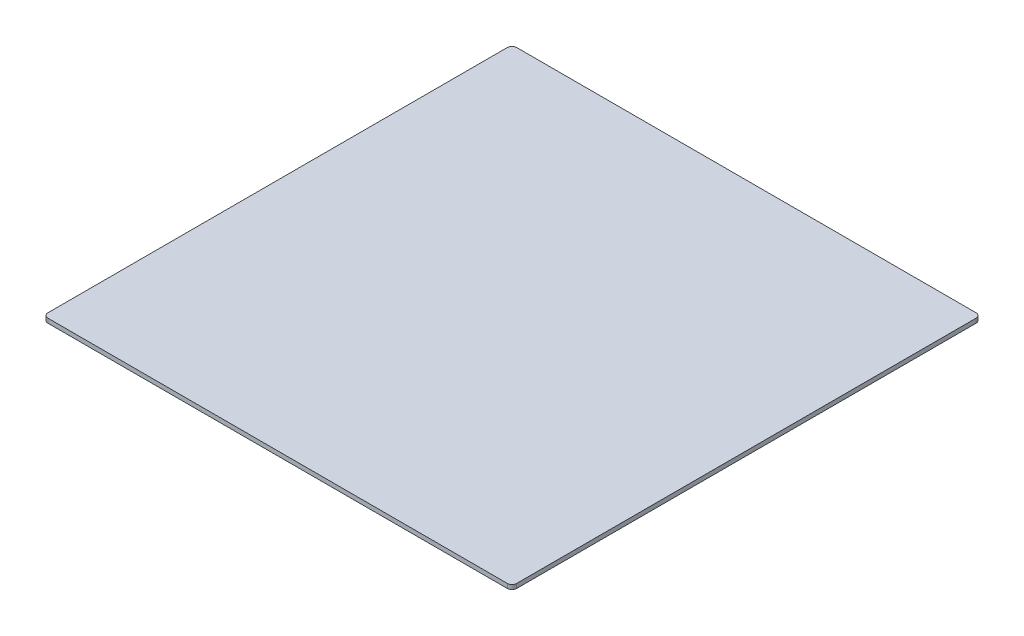
SolidWorks part; units mm, degrees
ref_plane "Front Plane" through (0, 0, 0) normal (0, 0, 1) x (1, 0, 0)
ref_plane "Top Plane" through (0, 0, 0) normal (0, 1, 0) x (1, 0, 0)
ref_plane "Right Plane" through (0, 0, 0) normal (1, 0, 0) x (0, 0, -1)
sketch "Sketch1" plane through (0, 0, 0) normal (0, 1, 0) x (1, 0, 0)
  line L5 (-50, 50) -> (50, 50)
  line L6 (-50, 50) -> (-50, -50)
  line L7 (-50, -50) -> (50, -50)
  line L8 (50, 50) -> (50, -50)
  line L9 (-50, 50) -> (50, -50) construction
  line L10 (-50, -50) -> (50, 50) construction
  point P0 (0, 0)
  dimension "D1" = 100
extrude "Boss-Extrude1" add sketch "Sketch1" along normal mid plane 0.9373
fillet "Fillet1" radius 1 4 edges at (50, 0, 50) (-50, 0, 50) (-50, 0, -50) (50, 0, -50)
